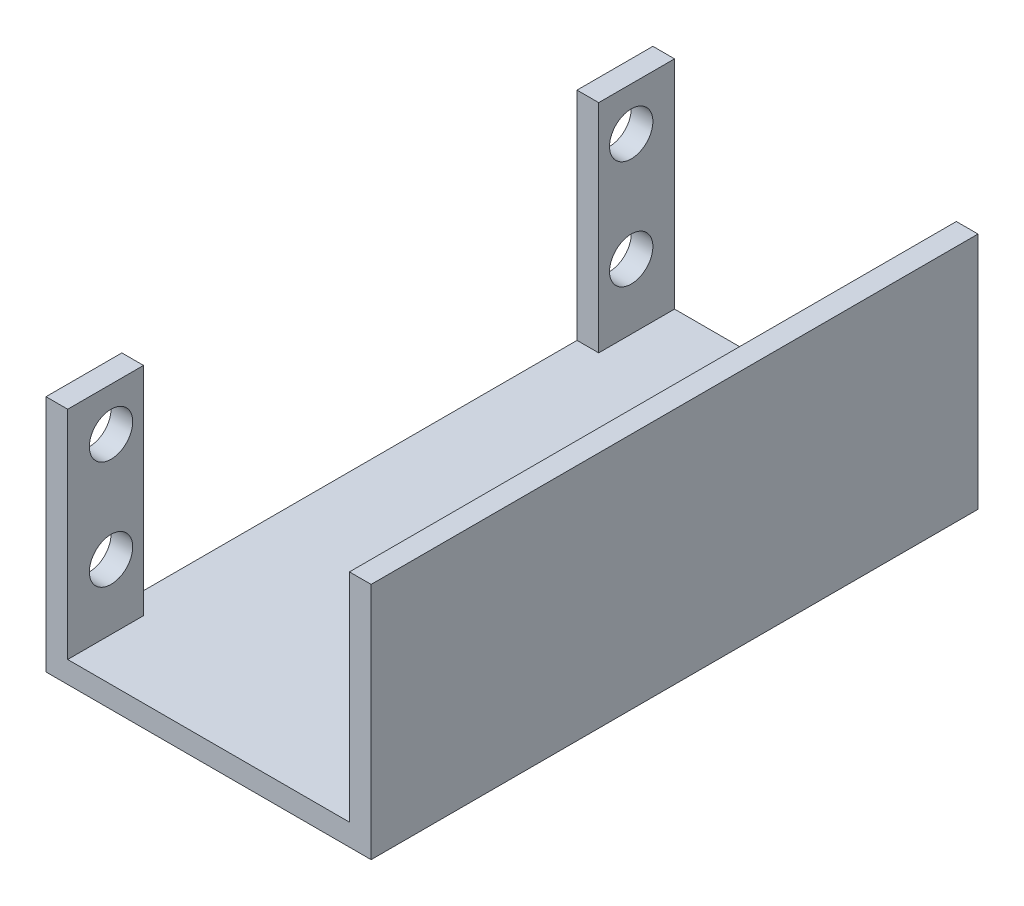
SolidWorks part; units mm, degrees
ref_plane "前视基准面" through (0, 0, 0) normal (0, 0, 1) x (1, 0, 0)
ref_plane "上视基准面" through (0, 0, 0) normal (0, 1, 0) x (1, 0, 0)
ref_plane "右视基准面" through (0, 0, 0) normal (1, 0, 0) x (0, 0, -1)
sketch "草图1" plane through (0, 0, 0) normal (0, 0, 1) x (1, 0, 0)
  line L1 (-15, -1) -> (15, -1)
  line L2 (-15, -1) -> (-15, 1)
  line L3 (-15, 1) -> (15, 1)
  line L4 (15, -1) -> (15, 1)
  line L5 (-15, -1) -> (15, 1) construction
  line L6 (-15, 1) -> (15, -1) construction
  line L7 (-15, 1) -> (-13, 1)
  line L8 (-15, 1) -> (-15, 21)
  line L9 (-15, 21) -> (-13, 21)
  line L10 (-13, 1) -> (-13, 21)
  line L11 (15, 1) -> (13, 1)
  line L12 (15, 1) -> (15, 21)
  line L13 (15, 21) -> (13, 21)
  line L14 (13, 1) -> (13, 21)
  point P0 (0, 0)
  dimension "D1" = 26
  dimension "D2" = 22
  dimension "D3" = 2
extrude "凸台-拉伸1" add sketch "草图1" along normal mid plane 56 contours L3 L10 L9 L8 | L1 L4 L3 L2 | L14 L3 L12 L13
sketch "草图2" plane through (0, 0, 0) normal (1, 0, 0) x (0, 0, -1)
  line L0 (-28, 21) -> (28, 21) construction
  line L1 (-21, 21) -> (21, 21)
  line L2 (-21, 21) -> (-21, 1)
  line L3 (-21, 1) -> (21, 1)
  line L4 (21, 21) -> (21, 1)
  line L5 (-28, -1) -> (28, -1) construction
  point P6 (0, 1)
  dimension "D1" = 42
  dimension "D2" = 2
extrude "切除-拉伸1" cut sketch "草图2" against normal through all
sketch "草图3" plane through (-15, 0, 0) normal (-1, 0, 0) x (0, 0, 1)
  line L0 (21, 1) -> (-21, 1) construction
  line L1 (0, 0) -> (0, 21) construction
  line L2 (28, 21) -> (-28, 21) construction
  circle A0 centre (-24, 17) radius 2
  circle A1 centre (-24, 7) radius 2
  circle A2 centre (24, 7) radius 2
  circle A3 centre (24, 17) radius 2
  dimension "D1" = 4
  dimension "D2" = 10
  dimension "D3" = 24
  dimension "D4" = 6
extrude "切除-拉伸3" cut sketch "草图3" against normal up to next
